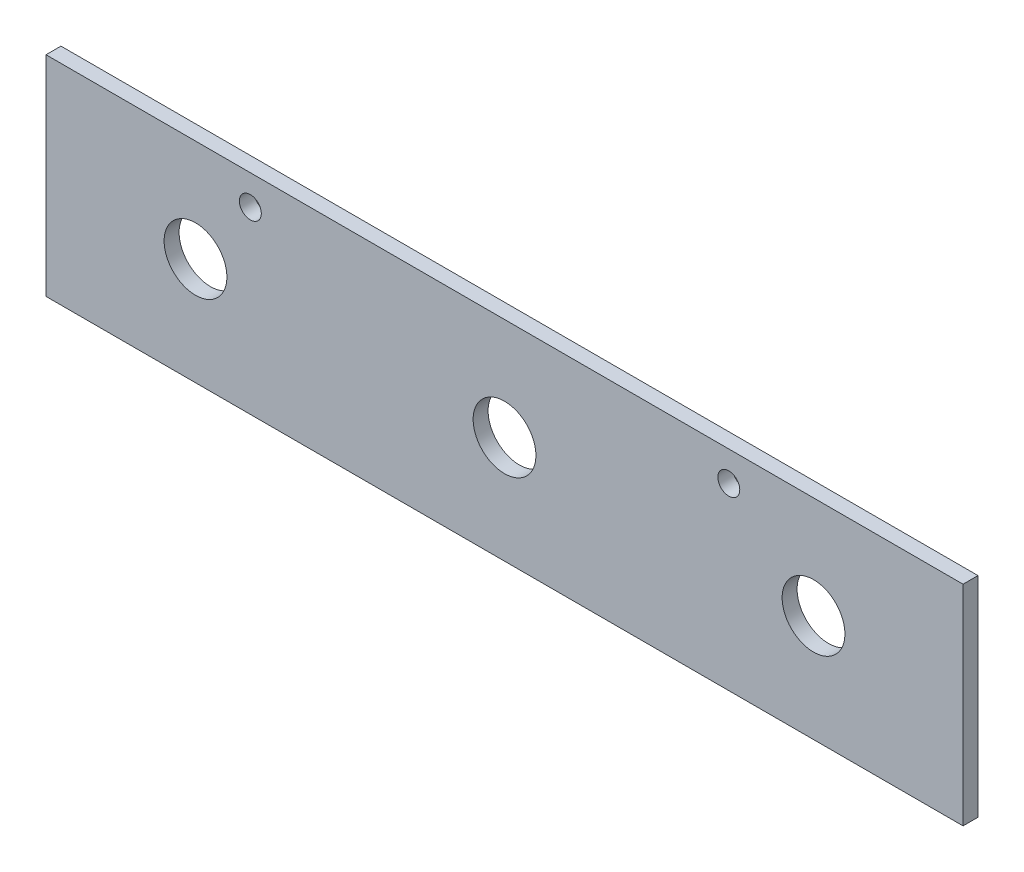
SolidWorks part; units mm, degrees
ref_plane "Front Plane" through (0, 0, 0) normal (0, 0, 1) x (1, 0, 0)
ref_plane "Top Plane" through (0, 0, 0) normal (0, 1, 0) x (1, 0, 0)
ref_plane "Right Plane" through (0, 0, 0) normal (1, 0, 0) x (0, 0, -1)
sketch "Three boss bores and blank gearbox fixing zones profile" plane through (0, 0, 0) normal (0, 0, 1) x (1, 0, 0)
  line L0 (-92, 7) -> (92, 7)
  line L1 (92, 7) -> (92, 49)
  line L2 (92, 49) -> (-92, 49)
  line L3 (-92, 49) -> (-92, 7)
  circle A0 centre (-62, 28.5) radius 6.3
  circle A1 centre (0, 28.5) radius 6.3
  circle A2 centre (62, 28.5) radius 6.3
  circle A3 centre (-51, 43) radius 2.2
  circle A4 centre (45, 43) radius 2.2
extrude "Three boss bores and blank gearbox fixing zones" add sketch "Three boss bores and blank gearbox fixing zones profile" along normal blind 3
